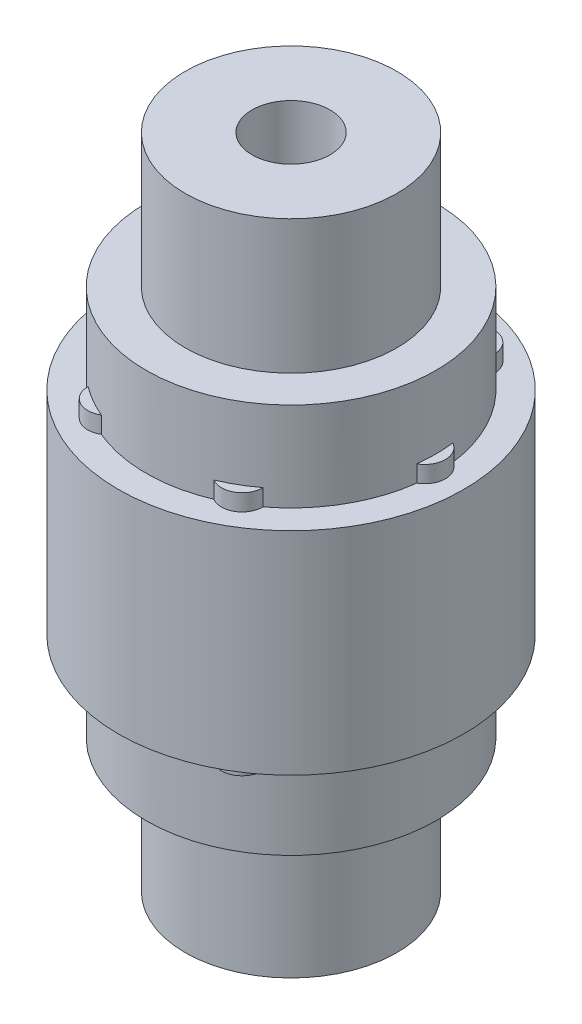
SolidWorks part; units mm, degrees
ref_plane "Front Plane" through (0, 0, 0) normal (0, 0, 1) x (1, 0, 0)
ref_plane "Top Plane" through (0, 0, 0) normal (0, 1, 0) x (1, 0, 0)
ref_plane "Right Plane" through (0, 0, 0) normal (1, 0, 0) x (0, 0, -1)
sketch "Sketch1" plane through (0, 0, 0) normal (0, 1, 0) x (1, 0, 0)
  circle A0 centre (0, 0) radius 19
  circle A1 centre (0, 0) radius 7
extrude "connector axle sleeve" add sketch "Sketch1" along normal mid plane 118
sketch "Sketch2" plane through (0, 0, 0) normal (0, 1, 0) x (1, 0, 0)
  circle A0 centre (0, 0) radius 31
  circle A1 centre (0, 0) radius 11
extrude "outer bolt flange" add sketch "Sketch2" along normal mid plane 38
sketch "Sketch3" plane through (0, 0, 0) normal (0, 1, 0) x (1, 0, 0)
  circle A0 centre (0, 0) radius 26
  circle A1 centre (0, 0) radius 9
extrude "stepped hub shoulder" add sketch "Sketch3" along normal mid plane 70
sketch "Sketch4" plane through (0, 0, 0) normal (0, 1, 0) x (1, 0, 0)
  circle A0 centre (24, 0) radius 3.7
extrude "bolt circle pad 1" add sketch "Sketch4" along normal mid plane 44
sketch "Sketch5" plane through (0, 0, 0) normal (0, 1, 0) x (1, 0, 0)
  circle A0 centre (12, 20.7846) radius 3.7
extrude "bolt circle pad 2" add sketch "Sketch5" along normal mid plane 44
sketch "Sketch6" plane through (0, 0, 0) normal (0, 1, 0) x (1, 0, 0)
  circle A0 centre (-12, 20.7846) radius 3.7
extrude "bolt circle pad 3" add sketch "Sketch6" along normal mid plane 44
sketch "Sketch7" plane through (0, 0, 0) normal (0, 1, 0) x (1, 0, 0)
  circle A0 centre (-24, 0) radius 3.7
extrude "bolt circle pad 4" add sketch "Sketch7" along normal mid plane 44
sketch "Sketch8" plane through (0, 0, 0) normal (0, 1, 0) x (1, 0, 0)
  circle A0 centre (-12, -20.7846) radius 3.7
extrude "bolt circle pad 5" add sketch "Sketch8" along normal mid plane 44
sketch "Sketch9" plane through (0, 0, 0) normal (0, 1, 0) x (1, 0, 0)
  circle A0 centre (12, -20.7846) radius 3.7
extrude "bolt circle pad 6" add sketch "Sketch9" along normal mid plane 44
